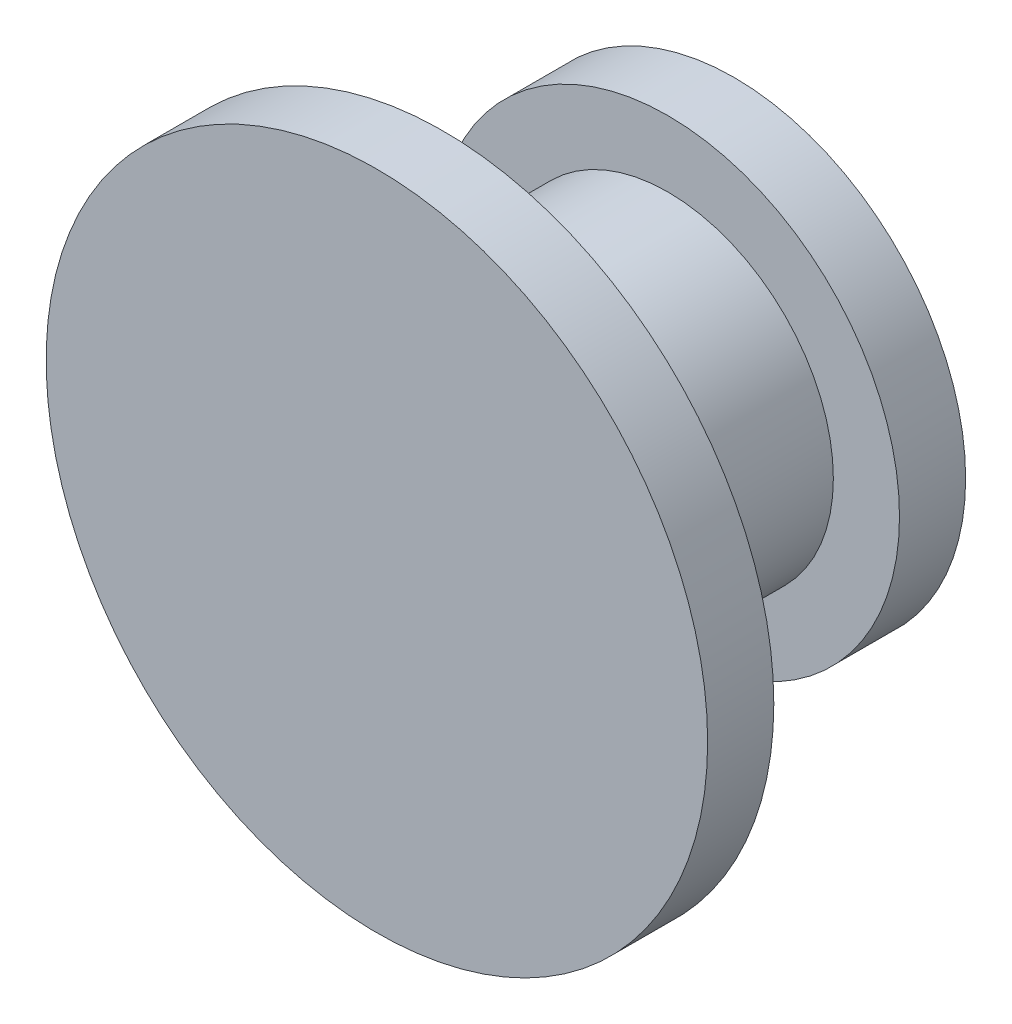
SolidWorks part; units mm, degrees
ref_plane "Ebene vorne" through (0, 0, 0) normal (0, 0, 1) x (1, 0, 0)
ref_plane "Ebene oben" through (0, 0, 0) normal (0, 1, 0) x (1, 0, 0)
ref_plane "Ebene rechts" through (0, 0, 0) normal (1, 0, 0) x (0, 0, -1)
sketch "Skizze1" plane through (0, 0, 0) normal (0, 0, 1) x (1, 0, 0)
  circle A0 centre (0, 0) radius 2.5
extrude "Aufsatz-Linear austragen1" add sketch "Skizze1" against normal up to surface (3.4 mm away) contours A0
sketch "Skizze2" plane through (0, 0, -3.4) normal (0, 0, -1) x (-1, 0, 0)
  circle A0 centre (0, 0) radius 3.5
  dimension "D1" = 7
extrude "Aufsatz-Linear austragen2" add sketch "Skizze2" along normal blind 1 contours A0
sketch "Skizze3" plane through (0, 0, 0) normal (0, 0, 1) x (1, 0, 0)
  circle A0 centre (0, 0) radius 5
  dimension "D1" = 10
extrude "Aufsatz-Linear austragen3" add sketch "Skizze3" along normal blind 1 contours A0
